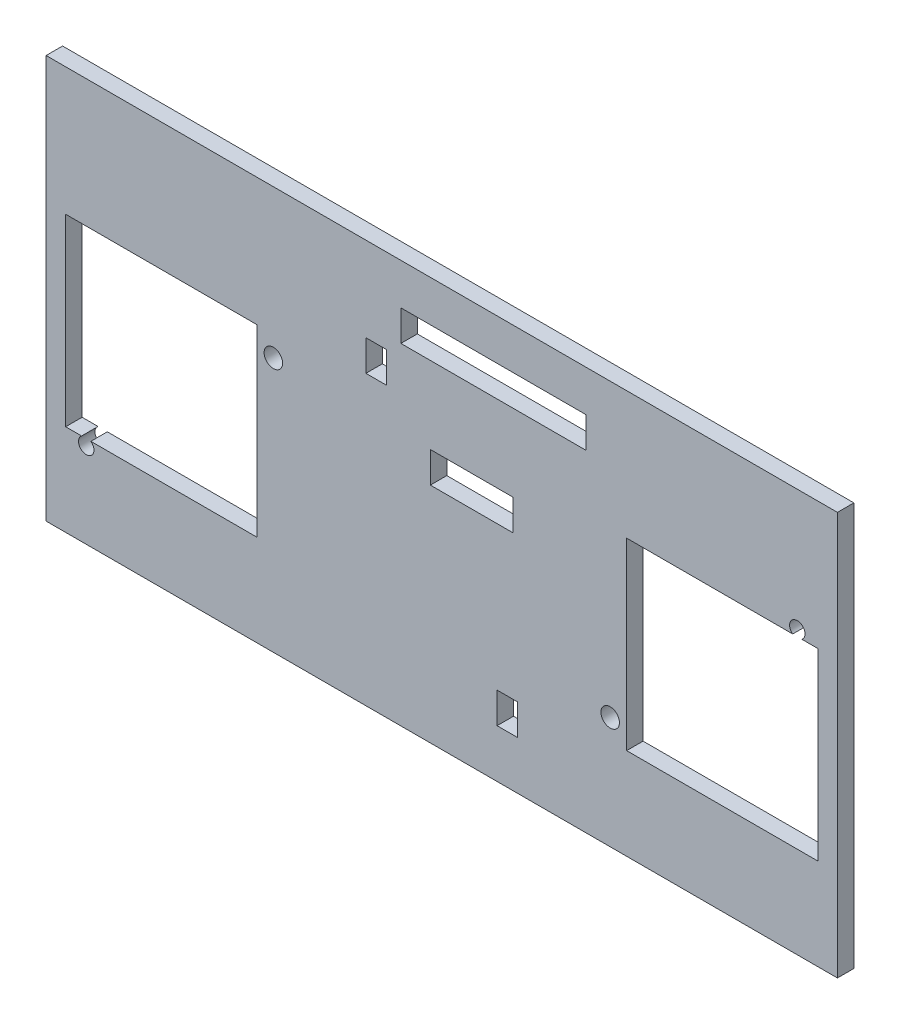
SolidWorks part; units mm, degrees
ref_plane "前视基准面" through (0, 0, 0) normal (0, 0, 1) x (1, 0, 0)
ref_plane "上视基准面" through (0, 0, 0) normal (0, 1, 0) x (1, 0, 0)
ref_plane "右视基准面" through (0, 0, 0) normal (1, 0, 0) x (0, 0, -1)
other "Configuration Table"
sketch "草图1" plane through (0, 0, 0) normal (0, 0, 1) x (1, 0, 0)
  line L0 (-18.08, 8.09) -> (-18.08, -9.61) construction
  line L1 (13.08, -14.61) -> (-13.08, -14.61) construction
  line L2 (38.48, -18.61) -> (-38.48, -18.61)
  line L3 (38.48, -18.61) -> (38.48, 20.61)
  line L4 (38.48, 20.61) -> (-38.48, 20.61)
  line L5 (-38.48, -18.61) -> (-38.48, 20.61)
  line L6 (-36.48, -9.61) -> (-36.48, 8.09) construction
  line L7 (36.48, 8.09) -> (36.48, -9.61) construction
  line L8 (-13.08, 14.61) -> (-2.78, 14.61) construction
  line L9 (-36.48, 8.09) -> (-18.08, 8.09) construction
  line L10 (-3.98, 16.61) -> (14.02, 16.61)
  line L11 (-3.98, 16.61) -> (-3.98, 13.61)
  line L12 (-3.98, 13.61) -> (14.02, 13.61)
  line L13 (14.02, 16.61) -> (14.02, 13.61)
  line L14 (-36.58, 8.19) -> (-17.98, 8.19)
  line L15 (-36.58, 8.19) -> (-36.58, -9.71)
  line L16 (-36.58, -9.71) -> (-17.98, -9.71)
  line L17 (-17.98, 8.19) -> (-17.98, -9.71)
  line L18 (17.98, 8.19) -> (36.58, 8.19)
  line L19 (17.98, 8.19) -> (17.98, -9.71)
  line L20 (17.98, -9.71) -> (36.58, -9.71)
  line L21 (36.58, 8.19) -> (36.58, -9.71)
  line L22 (-18.08, -9.61) -> (-36.48, -9.61) construction
  line L23 (36.48, -9.61) -> (18.08, -9.61) construction
  line L24 (18.08, 8.09) -> (36.48, 8.09) construction
  line L25 (18.08, -9.61) -> (18.08, 8.09) construction
  line L26 (-2.78, 15.8642) -> (-2.78, 14.8642) construction
  circle A0 centre (-16.38, 6.19) radius 0.9 construction
  circle A1 centre (16.38, -7.71) radius 0.9 construction
  circle A2 centre (-16.38, 6.19) radius 0.9
  circle A3 centre (16.38, -7.71) radius 0.9
  dimension "D1" = 4
  dimension "D2" = 2
  dimension "D3" = 2
  dimension "D4" = 6
  dimension "D5" = 0.1
  dimension "D6" = 0.1
  dimension "D7" = 0.1
  dimension "D8" = 0.1
  dimension "D9" = 0.1
  dimension "D10" = 0.1
  dimension "D11" = 0.1
  dimension "D12" = 0.1
  dimension "D13" = 4
  dimension "D14" = 18
  dimension "D15" = 1.2
  dimension "D16" = 3
extrude "凸台-拉伸1" add sketch "草图1" along normal blind 1.6
sketch "草图2" plane through (0, 0, 1.6) normal (0, 0, 1) x (1, 0, 0)
  circle A0 centre (34.58, 8.79) radius 0.75
  circle A1 centre (-34.58, -10.31) radius 0.75
extrude "切除-拉伸1" cut sketch "草图2" against normal blind 1.6
sketch "草图3" plane through (0, 0, 1.6) normal (0, 0, 1) x (1, 0, 0)
  line L0 (5.38, -13.91) -> (17.23, -13.91) construction
  line L1 (7.38, -13.91) -> (5.38, -13.91)
  line L2 (7.38, -13.91) -> (7.38, -10.91)
  line L3 (7.38, -10.91) -> (5.38, -10.91)
  line L4 (5.38, -13.91) -> (5.38, -10.91)
  line L5 (-5.38, 12.39) -> (-17.23, 12.39) construction
  line L6 (-5.38, 9.39) -> (-7.38, 9.39)
  line L7 (-5.38, 9.39) -> (-5.38, 12.39)
  line L8 (-5.38, 12.39) -> (-7.38, 12.39)
  line L9 (-7.38, 9.39) -> (-7.38, 12.39)
  dimension "D1" = 2
  dimension "D2" = 2
extrude "切除-拉伸2" cut sketch "草图3" against normal blind 1.6
sketch "草图5" plane through (0, 0, 1.6) normal (0, 0, 1) x (1, 0, 0)
  line L1 (6.94, 3.11) -> (-1.11, 3.11)
  line L2 (6.94, 3.11) -> (6.94, 6.11)
  line L3 (6.94, 6.11) -> (-1.11, 6.11)
  line L4 (-1.11, 3.11) -> (-1.11, 6.11)
extrude "切除-拉伸3" cut sketch "草图5" against normal blind 10
